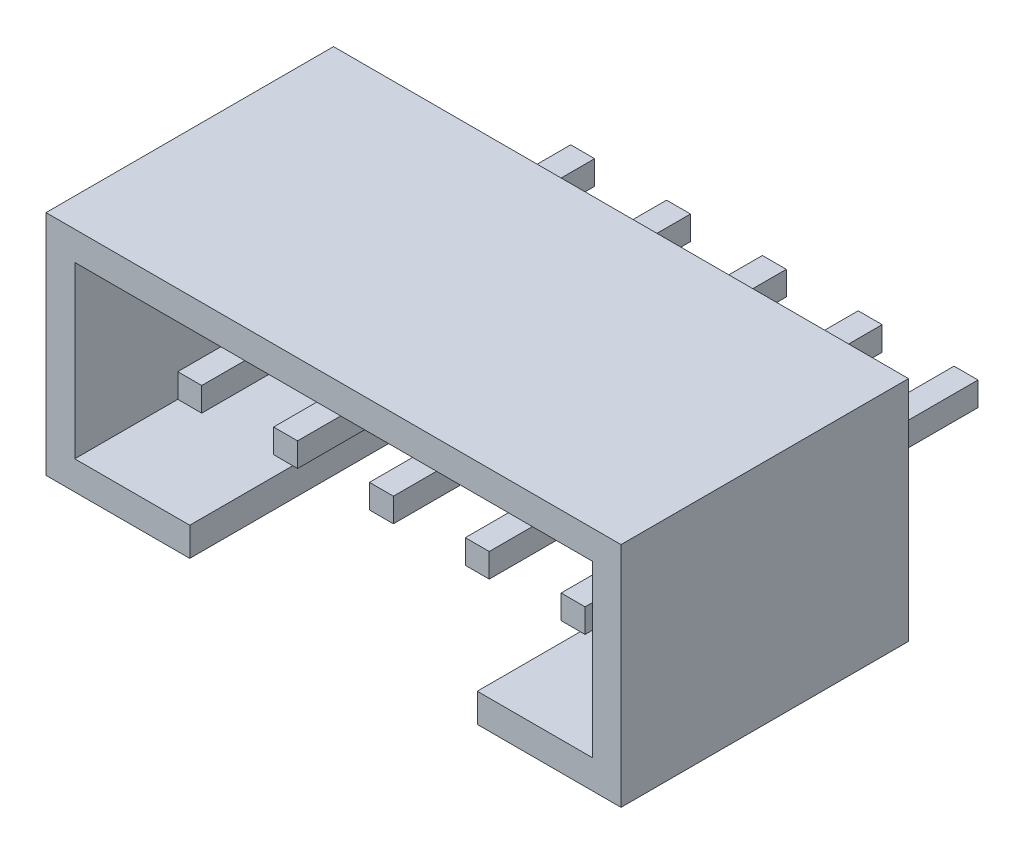
SolidWorks part; units mm, degrees
ref_plane "Front Plane" through (0, 0, 0) normal (0, 0, 1) x (1, 0, 0)
ref_plane "Top Plane" through (0, 0, 0) normal (0, 1, 0) x (1, 0, 0)
ref_plane "Right Plane" through (0, 0, 0) normal (1, 0, 0) x (0, 0, -1)
sketch "Sketch1" plane through (0, 0, 0) normal (0, 0, 1) x (1, 0, 0)
  line L1 (-6, 2.375) -> (6, 2.375)
  line L2 (-6, 2.375) -> (-6, -2.375)
  line L3 (-6, -2.375) -> (6, -2.375)
  line L4 (6, 2.375) -> (6, -2.375)
  line L5 (-6, 2.375) -> (6, -2.375) construction
  line L6 (-6, -2.375) -> (6, 2.375) construction
  point P0 (0, 0)
  dimension "D1" = 12
  dimension "D2" = 4.75
extrude "Boss-Extrude1" add sketch "Sketch1" along normal blind 1.8
sketch "Sketch2" plane through (0, 0, 1.8) normal (0, 0, 1) x (1, 0, 0)
  line L0 (-3, -2.375) -> (-3, -1.775)
  line L1 (-6, -2.375) -> (6, -2.375) construction
  line L2 (-3, -1.775) -> (-5.4, -1.775)
  line L3 (-5.4, -1.775) -> (-5.4, 1.775)
  line L4 (-5.4, 1.775) -> (5.4, 1.775)
  line L5 (0, 1.775) -> (0, 0) construction
  line L6 (-3, -2.375) -> (-6, -2.375)
  line L7 (-6, -2.375) -> (-6, 2.375)
  line L8 (-6, 2.375) -> (6, 2.375)
  line L9 (6, 2.375) -> (-6, 2.375) construction
  line L10 (6, -2.375) -> (6, 2.375)
  line L11 (3, -2.375) -> (6, -2.375)
  line L12 (3, -2.375) -> (3, -1.775)
  line L13 (3, -1.775) -> (5.4, -1.775)
  line L14 (5.4, -1.775) -> (5.4, 1.775)
  point P22 (0, 2.375)
  dimension "D1" = 3
  dimension "D2" = 0.6
  dimension "D3" = 0.6
  dimension "D4" = 0.6
extrude "Boss-Extrude2" add sketch "Sketch2" along normal offset from surface (4.2 mm away) 6 up to face at (0, 0, 0)
sketch "Sketch3" plane through (0, 0, 1.8) normal (0, 0, 1) x (1, 0, 0)
  line L0 (-3, -2.375) -> (3, -2.375) construction
  line L1 (-4.25, -0.125) -> (-3.75, -0.125)
  line L2 (-4.25, -0.125) -> (-4.25, -0.625)
  line L3 (-4.25, -0.625) -> (-3.75, -0.625)
  line L4 (-3.75, -0.125) -> (-3.75, -0.625)
  point P4 (-4.25, -0.375)
  point P7 (-4, -0.625)
  dimension "D1" = 0.5
  dimension "D2" = 2
  dimension "D3" = 4
extrude "Boss-Extrude3" add sketch "Sketch3" along normal offset from surface 5 and the other way blind 5 up to face at (0, 0, 0)
pattern_linear "LPattern1" count 5 spacing 2 along (1, 0, 0) of "Boss-Extrude3"
